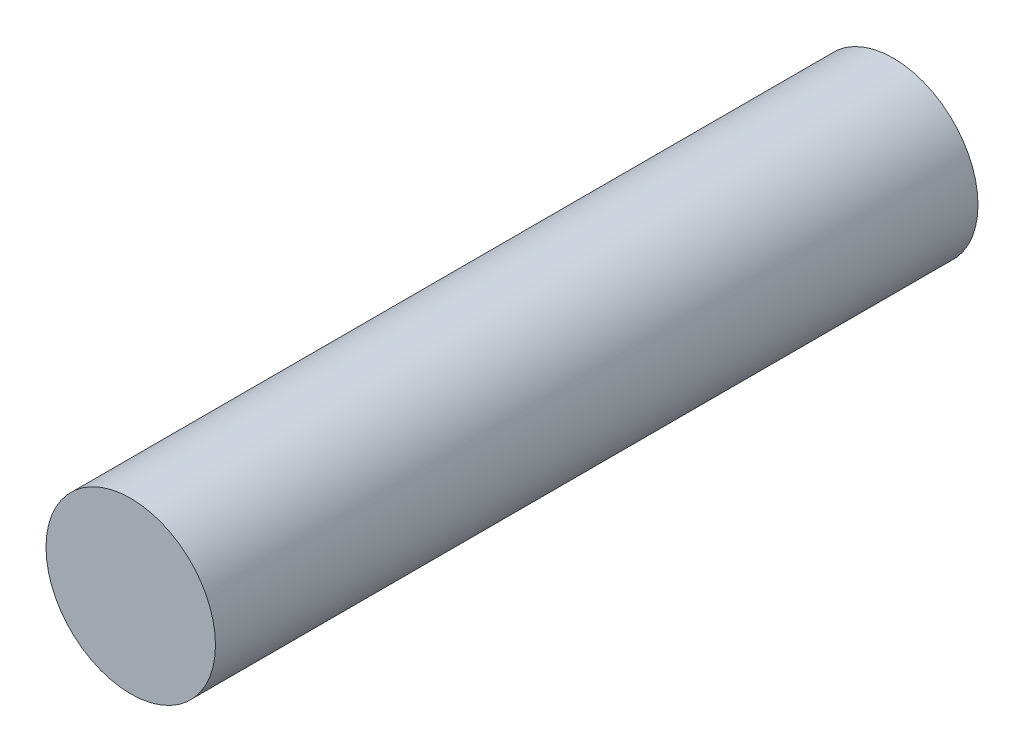
SolidWorks part; units mm, degrees
ref_plane "Front Plane" through (0, 0, 0) normal (0, 0, 1) x (1, 0, 0)
ref_plane "Top Plane" through (0, 0, 0) normal (0, 1, 0) x (1, 0, 0)
ref_plane "Right Plane" through (0, 0, 0) normal (1, 0, 0) x (0, 0, -1)
other "Configuration Table"
other "Center of Mass"
sketch "Sketch1" plane through (0, 0, 0) normal (0, 0, 1) x (1, 0, 0)
  circle A0 centre (0, 0) radius 2.7781
  dimension "D1" = 5.5562
extrude "Boss-Extrude1" add sketch "Sketch1" along normal blind 25
